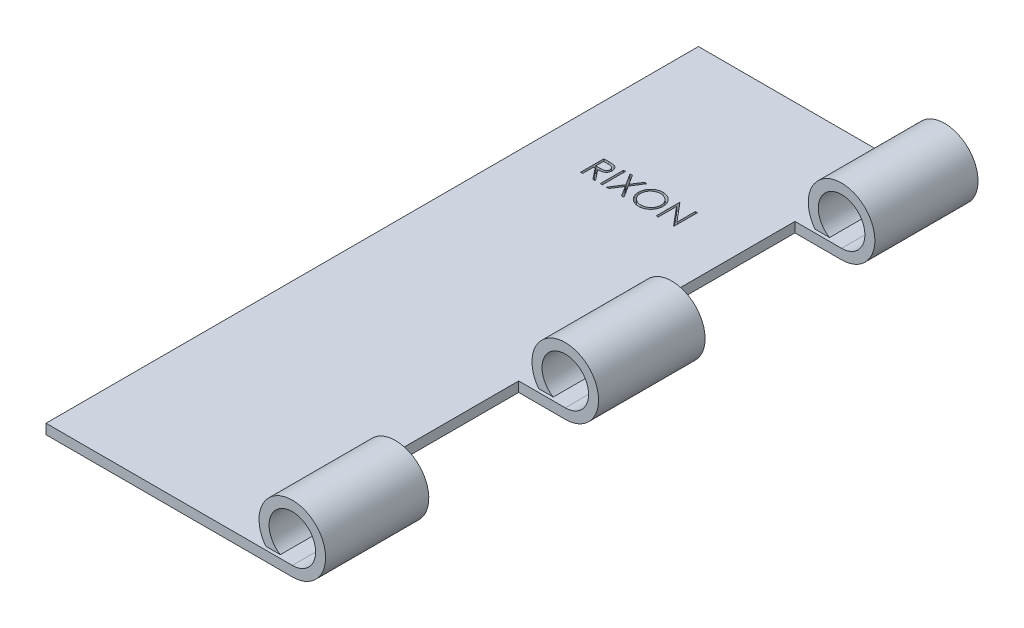
SolidWorks part; units mm, degrees
material "AISI 316 Stainless Steel Sheet (SS)"
ref_plane "Front Plane" through (0, 0, 0) normal (0, 0, 1) x (1, 0, 0)
ref_plane "Top Plane" through (0, 0, 0) normal (0, 1, 0) x (1, 0, 0)
ref_plane "Right Plane" through (0, 0, 0) normal (1, 0, 0) x (0, 0, -1)
sketch "Sketch1" plane through (0, 0, 0) normal (0, 0, 1) x (1, 0, 0)
  line L0 (0, 0) -> (30, 0)
  line L1 (30, 0) -> (32, 0)
  line L2 (32, 0) -> (37, 0)
  line L3 (37, 0) -> (37, 5) construction
  line L4 (33, 2) -> (35.1972, 2)
  line L5 (0, 1.5) -> (30, 1.5)
  line L6 (30, 1.5) -> (32, 1.5)
  line L7 (32, 1.5) -> (37, 1.5)
  line L8 (32, 2) -> (37, 2) construction
  line L9 (0, 1.5) -> (0, 0)
  arc A0 (37, 0) -> (33, 2) centre (37, 5) ccw
  arc A1 (37, 1.5) -> (35.1972, 2) centre (37, 5) ccw
  circle A2 centre (37, 5) radius 3.5 construction
  circle A3 centre (37, 5) radius 5 construction
  dimension "D1" = 30
  dimension "D2" = 2
  dimension "D3" = 5
  dimension "D4" = 5
  dimension "D5" = 2
  dimension "D6" = 1.5
extrude "Boss-Extrude1" add sketch "Sketch1" along normal blind 98
sketch "Sketch2" plane through (0, 0, 0) normal (0, -1, 0) x (1, 0, 0)
  line L0 (0, 0) -> (30, 0) construction
  line L2 (30, 0) -> (30, 15.5) construction
  line L3 (30, 0) -> (32, 0) construction
  line L4 (30, 15.5) -> (30, 41)
  line L5 (30, 15.5) -> (50.1658, 15.5)
  line L6 (50.1658, 15.5) -> (50.1658, 41)
  line L7 (50.1658, 41) -> (30, 41)
  line L8 (30, 98) -> (30, 82.5) construction
  line L9 (0, 98) -> (37, 98) construction
  line L11 (30, 82.5) -> (50.1658, 82.5)
  line L12 (30, 82.5) -> (30, 57)
  line L13 (30, 57) -> (50.1658, 57)
  line L14 (50.1658, 82.5) -> (50.1658, 57)
  dimension "D1" = 15.5
  dimension "D2" = 25.5
  dimension "D3" = 25.5
  dimension "D4" = 15.5
extrude "Cut-Extrude1" cut sketch "Sketch2" against normal through all
sketch "Sketch5" plane through (0, 1.5, 0) normal (0, 1, 0) x (1, 0, 0)
  text T0 "RIXON"
extrude "Cut-Extrude3" cut sketch "Sketch5" against normal blind 1
